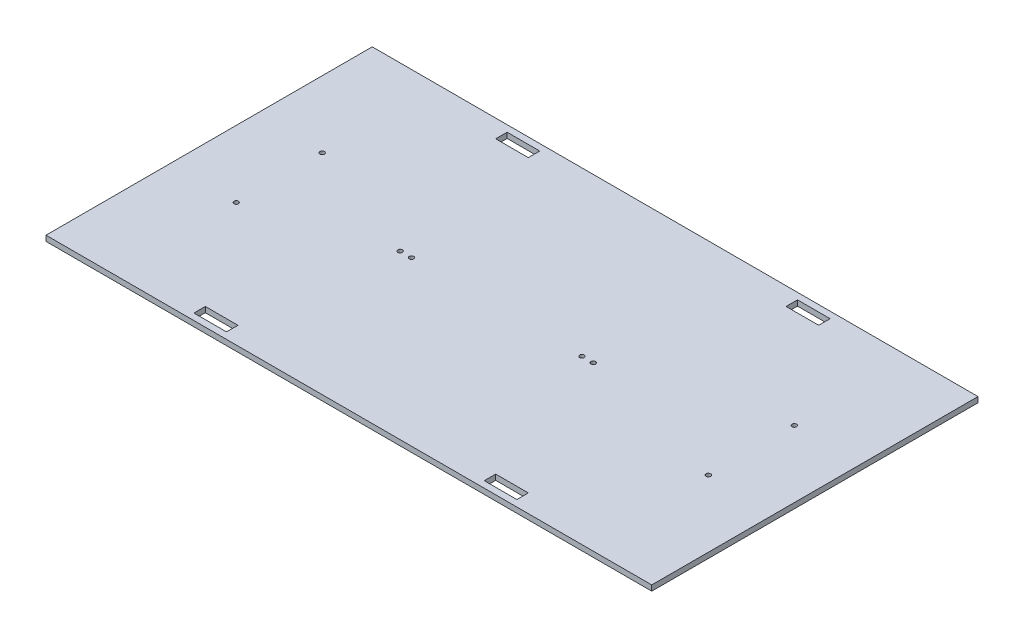
SolidWorks part; units mm, degrees
ref_plane "Front Plane" through (0, 0, 0) normal (0, 0, 1) x (1, 0, 0)
ref_plane "Top Plane" through (0, 0, 0) normal (0, 1, 0) x (1, 0, 0)
ref_plane "Right Plane" through (0, 0, 0) normal (1, 0, 0) x (0, 0, -1)
sketch "Sketch1" plane through (0, 0, 0) normal (0, 1, 0) x (1, 0, 0)
  line L1 (-278.5, 150) -> (278.5, 150)
  line L2 (-278.5, 150) -> (-278.5, -150)
  line L3 (-278.5, -150) -> (278.5, -150)
  line L4 (278.5, 150) -> (278.5, -150)
  line L5 (-278.5, 150) -> (278.5, -150) construction
  line L6 (-278.5, -150) -> (278.5, 150) construction
  point P0 (0, 0)
  dimension "D1" = 557
  dimension "D2" = 300
extrude "Boss-Extrude1" add sketch "Sketch1" along normal blind 5
sketch "Sketch2" plane through (0, 0, 0) normal (0, -1, 0) x (1, 0, 0)
  line L0 (64.36, -150) -> (64.36, 0) construction
  line L1 (278.5, -150) -> (-278.5, -150) construction
  line L2 (0, -150) -> (0, 150) construction
  line L3 (-278.5, 150) -> (278.5, 150) construction
  line L4 (64.36, 0) -> (74.7319, 0) construction
  circle A0 centre (64.36, 0) radius 2.1
  circle A1 centre (74.7319, 0) radius 2.1
  circle A2 centre (-92.5902, -0.1508) radius 2.1
  circle A3 centre (-102.9955, -0.1508) radius 2.1
  dimension "D1" = 4.2
  dimension "D4" = 4.2
  dimension "D2" = 150
  dimension "D3" = 64.36
extrude "Cut-Extrude1" cut sketch "Sketch2" against normal blind 10
sketch "Sketch3" plane through (0, 0, 0) normal (0, -1, 0) x (1, 0, 0)
  line L0 (278.5, -150) -> (-278.5, -150) construction
  line L1 (-278.5, -150) -> (-278.5, 150) construction
  line L2 (0, 150) -> (0, -150) construction
  line L3 (-278.5, 150) -> (278.5, 150) construction
  circle A0 centre (-217.06, -42.52) radius 2.1
  circle A1 centre (-217.06, 36.48) radius 2.1
  circle A2 centre (217.06, 36.48) radius 2.1
  circle A3 centre (217.06, -42.52) radius 2.1
  dimension "D1" = 4.2
  dimension "D2" = 4.2
  dimension "D3" = 107.48
  dimension "D4" = 61.44
  dimension "D5" = 79
extrude "Cut-Extrude2" cut sketch "Sketch3" against normal blind 10
sketch "Sketch4" plane through (0, 0, 0) normal (0, -1, 0) x (1, 0, 0)
  line L0 (278.5, 150) -> (278.5, -150) construction
  line L1 (148.5, 133.5) -> (118.5, 133.5)
  line L2 (148.5, 133.5) -> (148.5, 144)
  line L3 (148.5, 144) -> (118.5, 144)
  line L4 (118.5, 133.5) -> (118.5, 144)
  line L5 (-278.5, 150) -> (278.5, 150) construction
  line L6 (0, -150) -> (0, 150) construction
  line L7 (278.5, -150) -> (-278.5, -150) construction
  line L8 (-118.5, 133.5) -> (-118.5, 144)
  line L9 (-148.5, 144) -> (-118.5, 144)
  line L10 (-148.5, 133.5) -> (-148.5, 144)
  line L11 (-148.5, 133.5) -> (-118.5, 133.5)
  line L12 (278.5, 0) -> (-278.5, 0) construction
  line L13 (-278.5, -150) -> (-278.5, 150) construction
  line L14 (-148.5, -133.5) -> (-118.5, -133.5)
  line L15 (-148.5, -133.5) -> (-148.5, -144)
  line L16 (-148.5, -144) -> (-118.5, -144)
  line L17 (-118.5, -133.5) -> (-118.5, -144)
  line L18 (118.5, -133.5) -> (118.5, -144)
  line L19 (148.5, -144) -> (118.5, -144)
  line L20 (148.5, -133.5) -> (148.5, -144)
  line L21 (148.5, -133.5) -> (118.5, -133.5)
  dimension "D1" = 30
  dimension "D2" = 10.5
  dimension "D3" = 130
  dimension "D4" = 6
extrude "Cut-Extrude3" cut sketch "Sketch4" against normal blind 10
